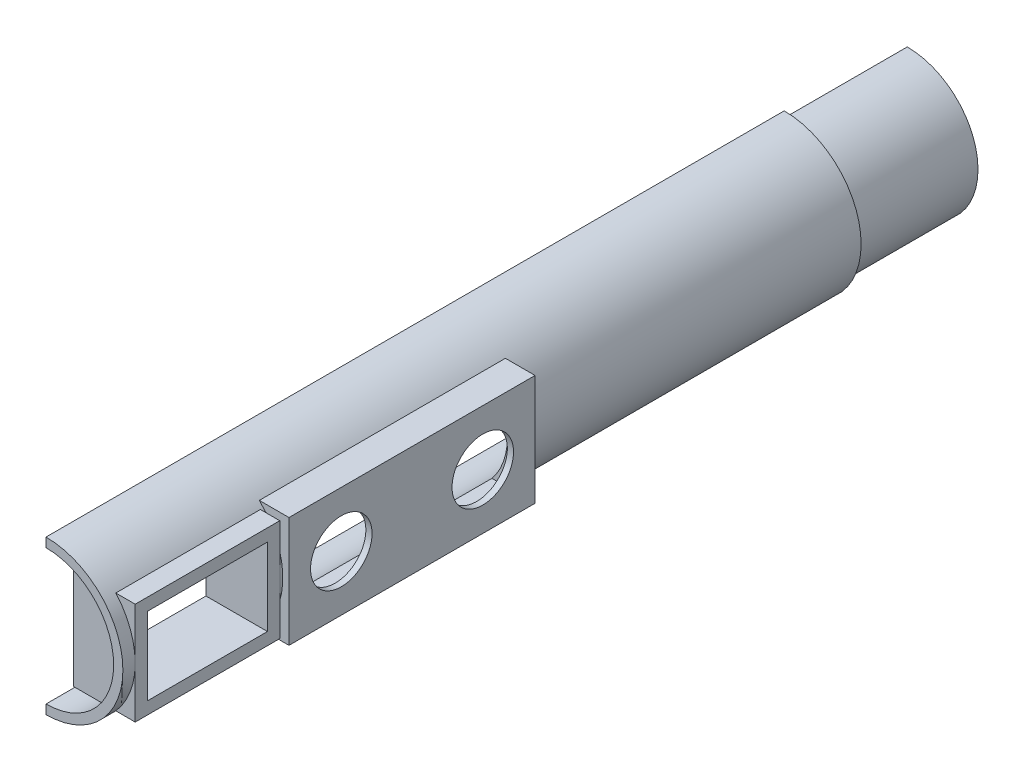
SolidWorks part; units mm, degrees
ref_plane "Front Plane" through (0, 0, 0) normal (0, 0, 1) x (1, 0, 0)
ref_plane "Top Plane" through (0, 0, 0) normal (0, 1, 0) x (1, 0, 0)
ref_plane "Right Plane" through (0, 0, 0) normal (1, 0, 0) x (0, 0, -1)
sketch "Sketch1" plane through (0, 0, 0) normal (0, 0, 1) x (1, 0, 0)
  line L0 (0, 259.8084) -> (0, 0) construction
  line L1 (0, 0) -> (-15.3, 0)
  line L2 (0, 0) -> (0, 180)
  line L3 (0, 180) -> (-15.3, 180)
  line L4 (-15.3, 0) -> (-15.3, 180)
  line L6 (-12.3, 0) -> (0, 0)
  line L7 (-12.3, 0) -> (-12.3, -20)
  line L8 (-12.3, -20) -> (0, -20)
  line L9 (0, 0) -> (0, -20)
  dimension "D1" = 12.3
  dimension "D2" = 180
  dimension "D3" = 20
  dimension "D4" = 3
revolve "Revolve1" add sketch "Sketch1" angle 360 about L0
ref_plane "Plane1" through (0, 0, 15.3) normal (0, 0, 1) x (1, 0, 0)
sketch "Sketch4" plane through (0, 0, 15.3) normal (0, 0, 1) x (1, 0, 0)
  circle A0 centre (0, 152.0713) radius 12.5
  dimension "D1" = 25
extrude "Boss-Extrude1" add sketch "Sketch4" along normal blind 120 and the other way blind 9
ref_plane "Plane2" through (-12.5, 0, 0) normal (-1, 0, 0) x (0, 0, 1)
sketch "Sketch6" plane through (-12.5, 0, 0) normal (-1, 0, 0) x (0, 0, 1)
  line L0 (109.3, 152.0713) -> (15.3, 152.0713) construction
  line L1 (71.3, 159.0713) -> (107.3, 159.0713)
  line L2 (71.3, 159.0713) -> (71.3, 145.0713)
  line L3 (71.3, 145.0713) -> (107.3, 145.0713)
  line L4 (107.3, 159.0713) -> (107.3, 145.0713)
  line L6 (15.3, -16.83) -> (15.3, 16.83) construction
  line L7 (69.3, 161.0713) -> (109.3, 161.0713)
  line L8 (109.3, 161.0713) -> (109.3, 143.0713)
  line L9 (69.3, 143.0713) -> (109.3, 143.0713)
  line L10 (69.3, 161.0713) -> (69.3, 143.0713)
  line L11 (135.3, 139.5713) -> (135.3, 164.5713) construction
  point P10 (107.3, 152.0713)
  point P16 (109.3, 152.0713)
  dimension "D1" = 36
  dimension "D2" = 14
  dimension "D4" = 26
  dimension "D3" = 2
extrude "Boss-Extrude2" add sketch "Sketch6" along normal blind 10 from offset 25 offset against normal yes
sketch "Sketch2" plane through (0, -20, 0) normal (0, -1, 0) x (1, 0, 0)
  circle A0 centre (0, 0) radius 10.8
  circle A1 centre (0, 0) radius 12.3 construction
  dimension "D1" = 1.5
extrude "Cut-Extrude1" cut sketch "Sketch2" against normal offset from surface (199 mm away) 1 up to face at (0, 180, 15.3)
sketch "Sketch5" plane through (0, 0, 135.3) normal (0, 0, 1) x (1, 0, 0)
  circle A0 centre (0, 152.0713) radius 11
  circle A1 centre (0, 152.0713) radius 12.5 construction
  dimension "D1" = 1.5
extrude "Cut-Extrude2" cut sketch "Sketch5" against normal blind 133
sketch "Sketch7" plane through (12.5, 0, 0) normal (1, 0, 0) x (0, 0, -1)
  line L1 (-107.3, 159.0713) -> (-71.3, 159.0713)
  line L2 (-107.3, 159.0713) -> (-107.3, 145.0713)
  line L3 (-107.3, 145.0713) -> (-71.3, 145.0713)
  line L4 (-71.3, 159.0713) -> (-71.3, 145.0713)
extrude "Cut-Extrude3" cut sketch "Sketch7" against normal blind 15
sketch "Sketch8" plane through (0, 0, 71.3) normal (0, 0, 1) x (1, 0, 0)
  line L0 (12.5, 159.0713) -> (12.5, 145.0713) construction
  line L1 (5.5, 163.0713) -> (0, 163.0713)
  line L2 (5.5, 163.0713) -> (5.5, 141.0713)
  line L3 (5.5, 141.0713) -> (0, 141.0713)
  line L4 (0, 163.0713) -> (0, 141.0713)
  arc A0 (5.5, 142.545) -> (5.5, 161.5975) centre (0, 152.0713) ccw
  point P4 (5.5, 152.0713)
  point P7 (12.5, 152.0713)
  arc M6 (8.4853, 159.0713) -> (8.4853, 145.0713) centre (0, 152.0713) cw
  dimension "D1" = 22
  dimension "D2" = 5.5
extrude "Boss-Extrude3" add sketch "Sketch8" against normal blind 6 from offset 11 contours L1 L4 L3 L2 | A0 L2 M6 offset against normal yes
sketch "Sketch10" plane through (12.5, 0, 0) normal (1, 0, 0) x (0, 0, -1)
  line L1 (-131.3, 158.3713) -> (-111.8, 158.3713)
  line L2 (-131.3, 158.3713) -> (-131.3, 145.7713)
  line L3 (-131.3, 145.7713) -> (-111.8, 145.7713)
  line L4 (-111.8, 158.3713) -> (-111.8, 145.7713)
  line L6 (-133.3, 160.3713) -> (-109.8, 160.3713)
  line L7 (-109.8, 160.3713) -> (-109.8, 143.7713)
  line L8 (-133.3, 143.7713) -> (-109.8, 143.7713)
  line L9 (-133.3, 160.3713) -> (-133.3, 143.7713)
  line L11 (-135.3, 164.5713) -> (-135.3, 139.5713) construction
  point P6 (-131.3, 152.0713)
  dimension "D1" = 19.5
  dimension "D2" = 12.6
  dimension "D3" = 2
  dimension "D4" = 2
extrude "Boss-Extrude5" add sketch "Sketch10" against normal blind 10
sketch "Sketch11" plane through (12.5, 0, 0) normal (1, 0, 0) x (0, 0, -1)
  line L1 (-131.3, 158.3713) -> (-111.8, 158.3713)
  line L2 (-131.3, 158.3713) -> (-131.3, 145.7713)
  line L3 (-131.3, 145.7713) -> (-111.8, 145.7713)
  line L4 (-111.8, 158.3713) -> (-111.8, 145.7713)
extrude "Cut-Extrude4" cut sketch "Sketch11" against normal blind 12
sketch "Sketch13" plane through (12.5, 0, 0) normal (1, 0, 0) x (0, 0, -1)
  line L0 (-107.3, 145.0713) -> (-107.3, 159.0713) construction
  line L1 (-109.3, 161.0713) -> (-69.3, 161.0713)
  line L2 (-109.3, 161.0713) -> (-109.3, 143.0713)
  line L3 (-109.3, 143.0713) -> (-69.3, 143.0713)
  line L4 (-69.3, 161.0713) -> (-69.3, 143.0713)
  line L10 (-109.3, 161.0713) -> (-109.3, 152.0713) construction
  line L11 (-109.3, 152.0713) -> (-69.3, 152.0713) construction
  circle A0 centre (-100.8, 152.0713) radius 5
  circle A2 centre (-77.8, 152.0713) radius 5
  dimension "D1" = 10
  dimension "D3" = 10
  dimension "D4" = 6.5
extrude "Boss-Extrude6" add sketch "Sketch13" along normal blind 1
sketch "Sketch15" plane through (0, 0, 0) normal (1, 0, 0) x (0, 0, -1)
  line L0 (-15.3, 55) -> (-15.3, -55) construction
  line L1 (15.3, 180) -> (-15.3, 180)
  line L2 (15.3, 180) -> (15.3, -23.6699)
  line L3 (15.3, -23.6699) -> (-15.3, -23.6699)
  line L4 (-15.3, 180) -> (-15.3, -23.6699)
extrude "Cut-Extrude7" cut sketch "Sketch15" against normal blind 39 and the other way blind 106
sketch "Sketch16" plane through (0, 0, 15.3) normal (0, 0, -1) x (-1, 0, 0)
  line L0 (0, 163.0713) -> (0, 141.0713) construction
  circle A0 centre (0, 152.0713) radius 12.5
extrude "Boss-Extrude7" add sketch "Sketch16" against normal blind 2
sketch "Sketch17" plane through (0, 0, 15.3) normal (0, 0, -1) x (-1, 0, 0)
  circle A0 centre (0, 152.0713) radius 11.5
  circle A1 centre (0, 152.0713) radius 10
  dimension "D1" = 23
  dimension "D2" = 1.5
extrude "Boss-Extrude8" add sketch "Sketch17" along normal blind 20
sketch "Sketch18" plane through (0, 0, 15.3) normal (0, 0, -1) x (-1, 0, 0)
  circle A0 centre (0, 152.0713) radius 10
extrude "Cut-Extrude8" cut sketch "Sketch18" against normal blind 2
sketch "Sketch9" plane through (0, 0, 0) normal (-1, 0, 0) x (0, 0, 1)
  line L0 (60.3, 152.0713) -> (54.3, 152.0713) construction
  line L1 (60.3, 163.0713) -> (60.3, 141.0713) construction
  line L2 (54.3, 163.0713) -> (54.3, 141.0713) construction
  circle A0 centre (57.05, 159.6713) radius 1.75
  circle A1 centre (57.05, 144.4713) radius 1.75
  dimension "D1" = 3.5
  dimension "D2" = 3.25
  dimension "D3" = 7.6
extrude "Boss-Extrude4" add sketch "Sketch9" along normal blind 2
sketch "Sketch19" plane through (0, 0, 135.3) normal (0, 0, 1) x (1, 0, 0)
  line L0 (0, 164.5713) -> (0, 139.5713)
  line L1 (13.5, 161.0713) -> (0, 161.0713)
  line L2 (8.6747, 161.0713) -> (13.5, 161.0713) construction
  line L3 (13.5, 161.0713) -> (13.5, 143.0713)
  line L4 (13.5, 143.0713) -> (0, 143.0713)
  line L6 (0, 161.701) -> (-2.1773, 161.701)
  line L7 (0, 161.701) -> (0, 142.5423)
  line L8 (0, 142.5423) -> (-2.1773, 142.5423)
  line L9 (-2.1773, 161.701) -> (-2.1773, 142.5423)
  circle A0 centre (0, 152.0713) radius 12.5 construction
  circle A1 centre (0, 152.0713) radius 9
  circle M1 centre (0, 152.0713) radius 11
  circle M2 centre (0, 152.0713) radius 12.5
extrude "Cut-Extrude10" cut sketch "Sketch19" against normal blind 182 contours L0 M2 M1 | A1 L9 L6 L0 L8 M1 | L9 A1
